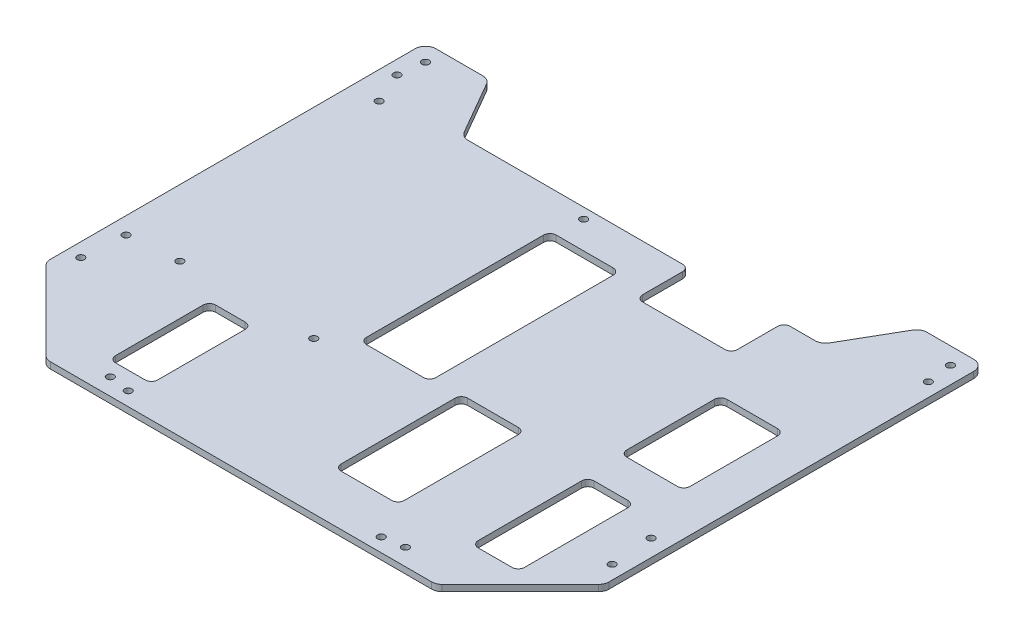
SolidWorks part; units mm, degrees
material "Acier non allié"
ref_plane "Front" through (0, 0, 0) normal (0, 0, 1) x (1, 0, 0)
ref_plane "Top" through (0, 0, 0) normal (0, 1, 0) x (1, 0, 0)
ref_plane "Right" through (0, 0, 0) normal (1, 0, 0) x (0, 0, -1)
sketch "Esquisse1" plane through (0, 0, 0) normal (0, 1, 0) x (1, 0, 0)
  line L0 (0, 0) -> (0, 1919.0564) construction
  line L1 (-92.5, 0) -> (92.5, 0)
  line L2 (92.5, 0) -> (132.5, 40)
  line L3 (132.5, 40) -> (132.5, 220)
  line L4 (132.5, 220) -> (102.5, 220)
  line L5 (102.5, 220) -> (85.1795, 190)
  line L6 (85.1795, 190) -> (-85.1795, 190)
  line L7 (-102.5, 220) -> (-85.1795, 190)
  line L8 (-132.5, 220) -> (-102.5, 220)
  line L9 (-132.5, 40) -> (-132.5, 220)
  line L10 (-92.5, 0) -> (-132.5, 40)
  point P12 (0, 190)
  dimension "D1" = 132.5
  dimension "D2" = 220
  dimension "D3" = 30
  dimension "D4" = 30
  dimension "D5" = 40
  dimension "D6" = 40
  dimension "D7" = 60
extrude "Boss.-Extru.1" add sketch "Esquisse1" along normal blind 3
fillet "Congé1" radius 5 10 edges at (132.5, 1.5, -220) (102.5, 1.5, -220) (85.1795, 1.5, -190) (-85.1795, 1.5, -190) (-102.5, 1.5, -220) (-132.5, 1.5, -220) (-132.5, 1.5, -40) (-92.5, 1.5, 0) (92.5, 1.5, 0) (132.5, 1.5, -40)
sketch "Esquisse2" plane through (0, 0, 0) normal (0, -1, 0) x (1, 0, 0)
  line L0 (0, 0) -> (0, -330.9968) construction
  line L1 (-90.4289, 0) -> (90.4289, 0) construction
  line L2 (-105.3868, -220) -> (-127.5, -220) construction
  line L3 (-132.5, -215) -> (-132.5, -42.0711) construction
  line L4 (-90.4289, 0) -> (90.4289, 0) construction
  line L5 (132.5, -42.0711) -> (132.5, -215) construction
  line L6 (-119.5, -185) -> (-22.5, -185) construction
  line L7 (82.2927, -190) -> (-82.2927, -190) construction
  line L8 (-132.5, -215) -> (-132.5, -42.0711) construction
  line L9 (-101, -72) -> (-37.5, -72) construction
  circle A0 centre (-70, -8) radius 1
  circle A1 centre (-124.5, -70) radius 1
  circle A2 centre (-124.5, -212) radius 1
  circle A3 centre (124.5, -212) radius 1
  circle A4 centre (124.5, -70) radius 1
  circle A5 centre (70, -8) radius 1
  circle A6 centre (126, -50) radius 1.5
  circle A7 centre (126, -200) radius 1.5
  circle A8 centre (-60, -6.5) radius 1.5
  circle A9 centre (60, -6.5) radius 1.5
  circle A10 centre (-126, -50) radius 1.5
  circle A11 centre (-126, -200) radius 1.5
  circle A12 centre (-119.5, -185) radius 1.5
  circle A13 centre (-22.5, -185) radius 1.5
  circle A14 centre (-101, -72) radius 1.5
  circle A15 centre (-37.5, -72) radius 1.5
  dimension "D3" = 2
  dimension "D6" = 2
  dimension "D9" = 2
  dimension "D12" = 3
  dimension "D15" = 3
  dimension "D16" = 3
  dimension "D17" = 3
  dimension "D24" = 3
  dimension "D27" = 3
  dimension "D31" = 3
  dimension "D32" = 3
  dimension "D36" = 3
  dimension "D37" = 3
  dimension "D1" = 70
  dimension "D2" = 8
  dimension "D4" = 124.5
  dimension "D5" = 70
  dimension "D7" = 8
  dimension "D8" = 8
  dimension "D10" = 50
  dimension "D11" = 6.5
  dimension "D13" = 15
  dimension "D14" = 6.5
  dimension "D18" = 10
  dimension "D19" = 6.5
  dimension "D20" = 6.5
  dimension "D21" = 10
  dimension "D22" = 50
  dimension "D23" = 6.5
  dimension "D25" = 15
  dimension "D26" = 6.5
  dimension "D28" = 97
  dimension "D29" = 5
  dimension "D30" = 13
  dimension "D33" = 63.5
  dimension "D34" = 113
  dimension "D35" = 18.5
extrude "Enlèv. mat.-Extru.1" cut sketch "Esquisse2" against normal through all
hole_wizard "Dégagement M31" positions "Esquisse3" profile "Esquisse4" hole size "M3" standard "ISO" end condition through all
sketch "Esquisse3" plane through (0, 0, 0) normal (0, -1, 0) x (-1, 0, 0)
  point P0 (-70, 8)
  point P3 (-124.5, 70)
  point P6 (-124.5, 212)
  point P9 (124.5, 212)
  point P12 (124.5, 70)
  point P15 (70, 8)
  point P18 (-126, 200)
  point P21 (-126, 50)
  point P24 (-60, 6.5)
  point P27 (60, 6.5)
  point P44 (126, 50)
  point P49 (126, 200)
  point P52 (101, 72)
  point P55 (37.5, 72)
  point P58 (119.5, 185)
  point P61 (22.5, 185)
sketch "Esquisse4" plane through (70, 0, -8) normal (1, 0, 0) x (0, 0, -1)
  line L0 (0, 0) -> (0, 3)
  line L1 (0, 3) -> (1.7, 3)
  line L2 (1.7, 3) -> (1.7, 0)
  line L5 (1.7, 0) -> (0, 0)
  line L11 (0, -6.35) -> (0, 107.95) construction
  dimension "Diamètre du perçage jusqu'au prochain" = 3.4
  dimension "Profondeur du perçage jusqu'au prochain" = 3
sketch "Esquisse5" plane through (0, 0, 0) normal (0, -1, 0) x (1, 0, 0)
  line L6 (82.2927, -190) -> (-82.2927, -190) construction
  line L7 (22.5, -190) -> (67.5, -190)
  line L20 (22.5, -190) -> (22.5, -165)
  line L21 (22.5, -165) -> (67.5, -165)
  line L22 (67.5, -190) -> (67.5, -165)
  line L23 (132.5, -42.0711) -> (132.5, -215) construction
  line L25 (-25.5, -172) -> (7.5, -172)
  line L26 (-25.5, -172) -> (-25.5, -82)
  line L27 (-25.5, -82) -> (7.5, -82)
  line L28 (7.5, -172) -> (7.5, -82)
  line L29 (-132.5, -215) -> (-132.5, -42.0711) construction
  line L30 (127.5, -220) -> (105.3868, -220) construction
  line L31 (84.5, -80) -> (106.5, -80)
  line L32 (84.5, -80) -> (84.5, -25)
  line L33 (84.5, -25) -> (106.5, -25)
  line L34 (106.5, -80) -> (106.5, -25)
  line L35 (-90.4289, 0) -> (90.4289, 0) construction
  line L38 (20.5, -84) -> (50.5, -84)
  line L39 (20.5, -84) -> (20.5, -24)
  line L40 (20.5, -24) -> (50.5, -24)
  line L41 (50.5, -84) -> (50.5, -24)
  line L42 (-77.5, -62.5) -> (-57.5, -62.5)
  line L43 (-77.5, -62.5) -> (-77.5, -15)
  line L44 (-77.5, -15) -> (-57.5, -15)
  line L45 (-57.5, -62.5) -> (-57.5, -15)
  line L46 (82.5, -145) -> (112.5, -145)
  line L47 (82.5, -145) -> (82.5, -97.5)
  line L48 (82.5, -97.5) -> (112.5, -97.5)
  line L49 (112.5, -145) -> (112.5, -97.5)
  dimension "D14" = 24
  dimension "D17" = 75
  dimension "D12" = 60
  dimension "D1" = 65
  dimension "D2" = 110
  dimension "D3" = 25
  dimension "D4" = 82
  dimension "D5" = 140
  dimension "D6" = 90
  dimension "D7" = 33
  dimension "D8" = 48
  dimension "D9" = 140
  dimension "D10" = 55
  dimension "D11" = 22
  dimension "D13" = 30
  dimension "D15" = 82
  dimension "D16" = 15
  dimension "D18" = 20
  dimension "D19" = 47.5
  dimension "D20" = 50
  dimension "D21" = 75
  dimension "D22" = 47.5
  dimension "D23" = 30
extrude "Enlèv. mat.-Extru.2" cut sketch "Esquisse5" against normal through all
fillet "Congé2" radius 3 24 edges at (67.5, 1.5, -190) (67.5, 1.5, -165) (22.5, 1.5, -165) (22.5, 1.5, -190) (106.5, 1.5, -80) (84.5, 1.5, -80) (84.5, 1.5, -25) (106.5, 1.5, -25) (7.5, 1.5, -82) (7.5, 1.5, -172) (-25.5, 1.5, -82) (-25.5, 1.5, -172) (50.5, 1.5, -84) (20.5, 1.5, -84) (50.5, 1.5, -24) (20.5, 1.5, -24) (-57.5, 1.5, -15) (-57.5, 1.5, -62.5) (-77.5, 1.5, -15) (-77.5, 1.5, -62.5) (112.5, 1.5, -97.5) (112.5, 1.5, -145) (82.5, 1.5, -97.5) (82.5, 1.5, -145)
equation "\"WIDTH\"= 300mm'Total width of the robot"
equation "\"LENGTH\"= 220mm'Total length of the robot"
equation "\"CUT_DEPTH\"= 45mm'Depth of the cut on the edges of the plate"
equation "\"Plate_th\"= 3mm'Thickness of the plate"
equation "\"D1\"= \"Plate_th\""
